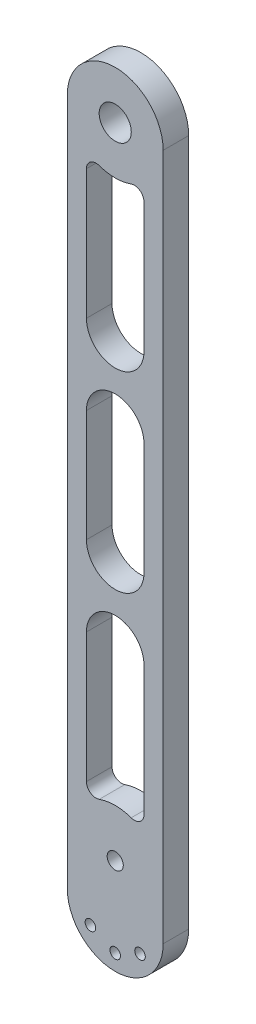
SolidWorks part; units mm, degrees
material "6061 合金"
ref_plane "前视基准面" through (0, 0, 0) normal (0, 0, 1) x (1, 0, 0)
ref_plane "上视基准面" through (0, 0, 0) normal (0, 1, 0) x (1, 0, 0)
ref_plane "右视基准面" through (0, 0, 0) normal (1, 0, 0) x (0, 0, -1)
other "Configuration Table"
sketch "草图1" plane through (0, 0, 0) normal (0, 0, 1) x (1, 0, 0)
  line L0 (-15, 0) -> (-15, -200)
  line L1 (15, 0) -> (15, -200)
  line L2 (-9, -16.9706) -> (-9, -57.5)
  line L3 (0, 0) -> (0, -200) construction
  line L4 (9, -16.9706) -> (9, -57.5)
  line L5 (0, -82.5) -> (0, -117.5) construction
  line L6 (9, -82.5) -> (9, -117.5)
  line L7 (-9, -82.5) -> (-9, -117.5)
  line L8 (15, -100) -> (-15, -100) construction
  line L11 (-9, -183.0294) -> (-9, -142.5)
  line L12 (9, -183.0294) -> (9, -142.5)
  circle A0 centre (0, 0) radius 5.025
  arc A1 (15, 0) -> (-15, 0) centre (0, 0) ccw
  circle A2 centre (0, -200) radius 2.525
  arc A3 (-15, -200) -> (15, -200) centre (0, -200) ccw
  arc A4 (-5, -14.1421) -> (5, -14.1421) centre (0, 0) ccw
  arc A5 (-9, -57.5) -> (9, -57.5) centre (0, -57.5) ccw
  arc A6 (9, -16.9706) -> (5, -14.1421) centre (6, -16.9706) ccw
  arc A7 (-5, -14.1421) -> (-9, -16.9706) centre (-6, -16.9706) ccw
  arc A8 (9, -82.5) -> (-9, -82.5) centre (0, -82.5) ccw
  arc A9 (-9, -117.5) -> (9, -117.5) centre (0, -117.5) ccw
  arc A12 (-5, -185.8579) -> (-9, -183.0294) centre (-6, -183.0294) cw
  arc A13 (-5, -185.8579) -> (5, -185.8579) centre (0, -200) cw
  arc A14 (9, -183.0294) -> (5, -185.8579) centre (6, -183.0294) cw
  arc A15 (-9, -142.5) -> (9, -142.5) centre (0, -142.5) cw
  point P16 (9, -12)
  point P19 (-9, -12)
  point P22 (0, -100)
  dimension "D1" = 10.05
  dimension "D2" = 200
  dimension "D3" = 30
  dimension "D4" = 5.05
  dimension "D6" = 3
  dimension "D7" = 15
  dimension "D10" = 25
  dimension "D5" = 6
  dimension "D8" = 6
  dimension "D12" = 35
extrude "凸台-拉伸1" add sketch "草图1" along normal blind 8
sketch "草图2" plane through (0, 0, 0) normal (0, 0, 1) x (1, 0, 0)
  line L0 (-15, -200) -> (-15, -215)
  line L1 (15, -200) -> (15, -215)
  line L2 (-7.7567, -221.3114) -> (0, -200) construction
  line L3 (0, -200) -> (0, -225) construction
  arc A0 (-15, -215) -> (15, -215) centre (0, -215) ccw
  arc A1 (-15, -200) -> (15, -200) centre (0, -200) ccw
  circle A2 centre (0, -200) radius 2.525 construction
  circle A3 centre (0, -215) radius 10 construction
  circle A4 centre (0, -225) radius 1.65
  circle A5 centre (-7.7567, -221.3114) radius 1.65
  circle A6 centre (7.7567, -221.3114) radius 1.65
  dimension "D1" = 15
  dimension "D2" = 20
  dimension "D3" = 3.3
  dimension "D4" = 3.3
  dimension "D5" = 3.3
  dimension "D6" = 20
extrude "凸台-拉伸2" add sketch "草图2" along normal through all
